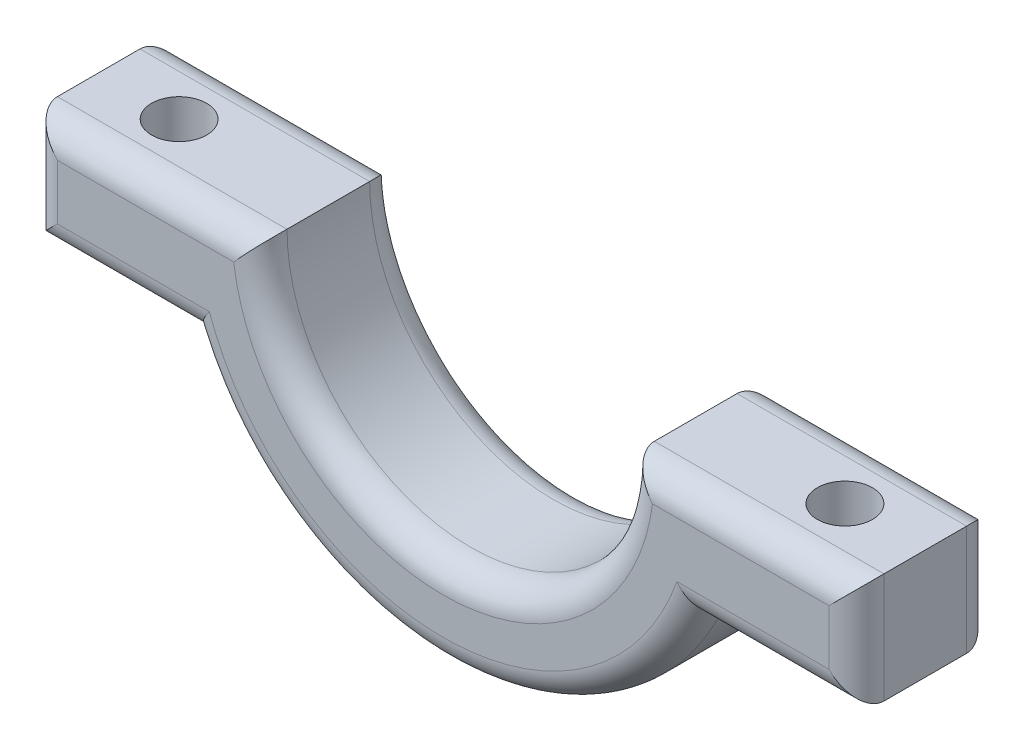
SolidWorks part; units mm, degrees
material "Plain Carbon Steel"
ref_plane "Front Plane" through (0, 0, 0) normal (0, 0, 1) x (1, 0, 0)
ref_plane "Top Plane" through (0, 0, 0) normal (0, 1, 0) x (1, 0, 0)
ref_plane "Right Plane" through (0, 0, 0) normal (1, 0, 0) x (0, 0, -1)
sketch "Sketch1" plane through (0, 0, 0) normal (0, 0, 1) x (1, 0, 0)
  line L0 (-20, 0) -> (-45, 0)
  line L1 (20, 0) -> (45, 0)
  line L2 (-45, 0) -> (-45, -12)
  line L3 (45, 0) -> (45, -12)
  line L4 (-45, -12) -> (-27.4955, -12)
  line L5 (45, -12) -> (27.4955, -12)
  line L6 (0, -1000) -> (0, 49000) construction
  arc A0 (20, 0) -> (-20, 0) centre (0, 0) cw
  arc A1 (27.4955, -12) -> (-27.4955, -12) centre (0, 0) cw
  dimension "D1" = 20
  dimension "D2" = 10
  dimension "D3" = 25
  dimension "D4" = 12
extrude "Boss-Extrude1" add sketch "Sketch1" along normal mid plane 15
fillet "Fillet2" radius 3 16 edges at (-32.5, 0, -7.5) (-45, -6, -7.5) (-36.2477, -12, -7.5) (0, -30, -7.5) (36.2477, -12, -7.5) (45, -6, -7.5) (32.5, 0, -7.5) (0, -20, -7.5) (32.5, 0, 7.5) (45, -6, 7.5) (36.2477, -12, 7.5) (0, -30, 7.5) (-36.2477, -12, 7.5) (-45, -6, 7.5) (-32.5, 0, 7.5) (0, -20, 7.5)
hole_wizard "Ø6.0mm Dowel Hole1" positions "Sketch3" profile "Sketch4" hole size "Ø6.0" standard "ANSI Metric" end condition through all
sketch "Sketch3" plane through (0, -12, 0) normal (0, -1, 0) x (-1, 0, 0)
  line L10 (0, -1000) -> (0, 49000) construction
  line L12 (36.2477, 4.5) -> (36.2477, 0) construction
  line L13 (45, 4.5) -> (27.4955, 4.5) construction
  point P0 (36.2477, 0)
  point P2 (-36.2477, 0)
sketch "Sketch4" plane through (-36.2477, -12, 0) normal (1, 0, 0) x (0, 0, -1)
  line L0 (0, 0) -> (0, 12)
  line L1 (0, 12) -> (3, 12)
  line L2 (3, 12) -> (3, 0)
  line L5 (3, 0) -> (0, 0)
  line L11 (0, -6.35) -> (0, 107.95) construction
  dimension "Thru Hole Dia." = 6
  dimension "Thru Hole Depth" = 12
